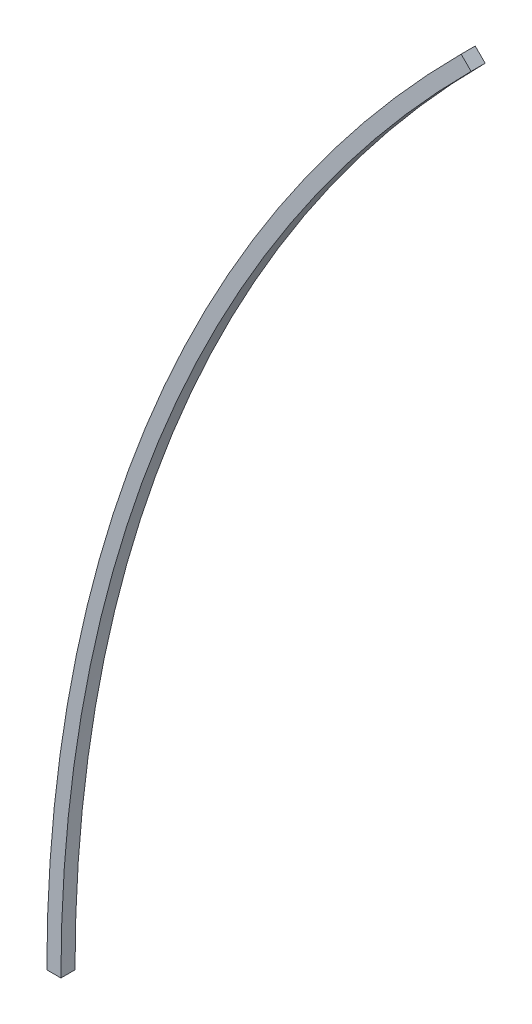
SolidWorks part; units mm, degrees
ref_plane "Front Plane" through (0, 0, 0) normal (0, 0, 1) x (1, 0, 0)
ref_plane "Top Plane" through (0, 0, 0) normal (0, 1, 0) x (1, 0, 0)
ref_plane "Right Plane" through (0, 0, 0) normal (1, 0, 0) x (0, 0, -1)
other "Configuration Table"
sketch "Sketch2" plane through (0, 0, 0) normal (0, 1, 0) x (1, 0, 0)
  line L0 (0, 0) -> (2540, 0)
  line L1 (2540, 0) -> (2540, -461.0711)
  dimension "D1" = 2540
ref_axis "Axis1" through (2540, 0, 0) along (0, 0, 1)
sketch "Sketch4" plane through (0, 0, 0) normal (0, 1, 0) x (1, 0, 0)
  line L0 (0, -260.5741) -> (0, 260.5741) construction
  line L1 (12.7, -12.7) -> (-12.7, -12.7)
  line L2 (12.7, -12.7) -> (12.7, 12.7)
  line L3 (12.7, 12.7) -> (-12.7, 12.7)
  line L4 (-12.7, -12.7) -> (-12.7, 12.7)
  line L5 (0, 0) -> (2540, 0) construction
  dimension "D1" = 12.7
  dimension "D2" = 12.7
  dimension "D3" = 12.7
  dimension "D4" = 12.7
revolve "Revolve1" add sketch "Sketch4" angle 45 about axis through (2540, 0, 0) along (0, 0, 1)
ref_point "Point1"
